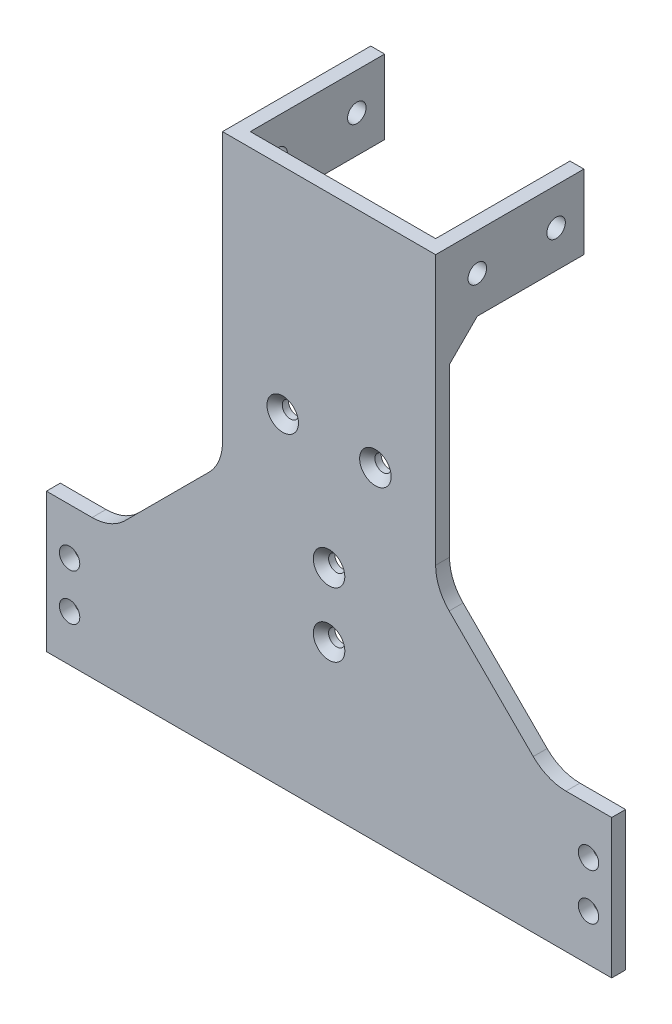
SolidWorks part; units mm, degrees
ref_plane "Front Plane" through (0, 0, 0) normal (0, 0, 1) x (1, 0, 0)
ref_plane "Top Plane" through (0, 0, 0) normal (0, 1, 0) x (1, 0, 0)
ref_plane "Right Plane" through (0, 0, 0) normal (1, 0, 0) x (0, 0, -1)
sketch "Sketch1" plane through (0, 0, 0) normal (0, 0, 1) x (1, 0, 0)
  line L0 (0, 15) -> (0, -15) construction
  line L1 (-61, -15) -> (61, -15)
  line L2 (-61, -15) -> (-61, 15)
  line L3 (-61, 15) -> (61, 15)
  line L4 (61, -15) -> (61, 15)
  line L5 (-61, -15) -> (61, 15) construction
  line L6 (-61, 15) -> (61, -15) construction
  line L7 (-61, 0) -> (61, 0) construction
  circle A0 centre (-56, 5) radius 2.2
  circle A1 centre (-56, -5) radius 2.2
  circle A2 centre (56, -5) radius 2.2
  circle A3 centre (56, 5) radius 2.2
  point P0 (0, 0)
  dimension "D5" = 4.4
  dimension "D1" = 122
  dimension "D2" = 5
  dimension "D3" = 10
  dimension "D4" = 5
extrude "Boss-Extrude1" add sketch "Sketch1" along normal blind 3
sketch "Sketch2" plane through (0, 0, 3) normal (0, 0, 1) x (1, 0, 0)
  line L0 (61, 15) -> (-61, 15) construction
  line L1 (-23, 15) -> (23, 15)
  line L2 (-23, 15) -> (-23, 101.2)
  line L3 (-23, 101.2) -> (23, 101.2)
  line L4 (23, 15) -> (23, 101.2)
  line L5 (0, 101.2) -> (0, 15) construction
  line L6 (-23, 57) -> (23, 57) construction
  circle A0 centre (0, 17.3) radius 1.75
  circle A1 centre (10, 54.9) radius 1.75
  circle A2 centre (0, 31.2) radius 1.75
  circle A3 centre (-10, 54.9) radius 1.75
  dimension "D4" = 3.5
  dimension "D5" = 3.5
  dimension "D9" = 3.5
  dimension "D1" = 0
  dimension "D2" = 70
  dimension "D3" = 42
  dimension "D6" = 10
  dimension "D7" = 46
  dimension "D8" = 37.6
  dimension "D10" = 23.7
  dimension "D11" = 2.1
extrude "Boss-Extrude2" add sketch "Sketch2" against normal blind 3
sketch "Sketch3" plane through (0, 0, 3) normal (0, 0, 1) x (1, 0, 0)
  line L0 (-47, 15) -> (-23, 39)
  line L1 (-23, 15) -> (-61, 15) construction
  line L2 (-23, 101.2) -> (-23, 15) construction
  line L3 (-23, 39) -> (-23, 15)
  line L4 (-23, 15) -> (-47, 15)
  line L5 (0, 101.2) -> (0, 0) construction
  line L6 (23, 101.2) -> (-23, 101.2) construction
  line L7 (23, 39) -> (23, 15)
  line L8 (47, 15) -> (23, 39)
  line L9 (23, 15) -> (47, 15)
  dimension "D1" = 24
  dimension "D2" = 24
extrude "Boss-Extrude3" add sketch "Sketch3" against normal blind 3
fillet "Fillet1" radius 10 4 edges at (47, 15, 1.5) (23, 39, 1.5) (-47, 15, 1.5) (-23, 39, 1.5)
chamfer "Chamfer1" distance 1.65 angle 45 4 edges at (11.75, 54.9, 3) (-11.75, 54.9, 3) (1.75, 17.3, 3) (1.75, 31.2, 3)
sketch "Sketch4" plane through (23, 0, 0) normal (1, 0, 0) x (0, 0, -1)
  line L0 (14.5, 101.2) -> (14.5, 85.2) construction
  line L1 (-3, 101.2) -> (29, 101.2)
  line L2 (-3, 101.2) -> (-3, 85.2)
  line L3 (-3, 85.2) -> (29, 85.2)
  line L4 (29, 101.2) -> (29, 85.2)
  line L5 (29, 93.2) -> (-3, 93.2) construction
  circle A2 centre (23, 93.2) radius 2
  circle A3 centre (6, 93.2) radius 2
  dimension "D3" = 4
  dimension "D1" = 32
  dimension "D2" = 14.5
  dimension "D4" = 16
  dimension "D5" = 6
extrude "Boss-Extrude4" add sketch "Sketch4" against normal blind 3
mirror "Mirror1" about plane through (0, 0, 0) normal (1, 0, 0) of "Boss-Extrude4"
chamfer "Chamfer2" distance 6 angle 45 2 edges at (-21.5, 85.2, 0) (21.5, 85.2, 0)
